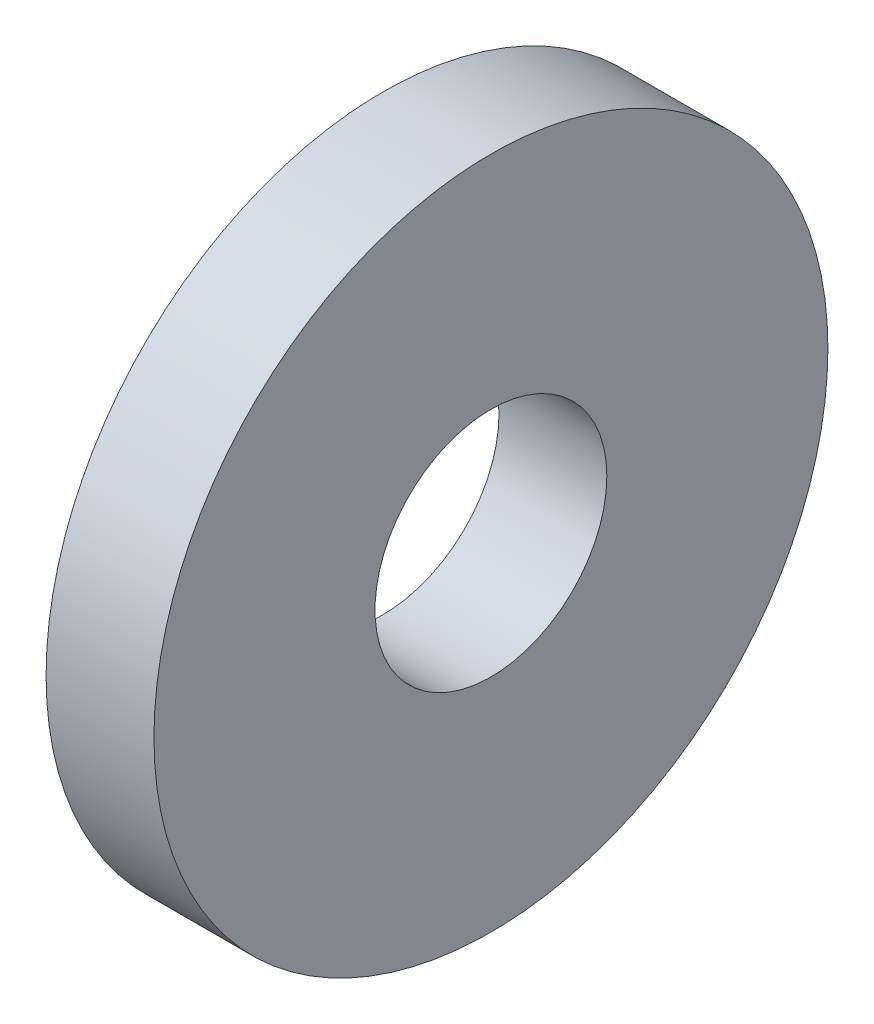
SolidWorks part; units mm, degrees
ref_plane "Front Plane" through (0, 0, 0) normal (0, 0, 1) x (1, 0, 0)
ref_plane "Top Plane" through (0, 0, 0) normal (0, 1, 0) x (1, 0, 0)
ref_plane "Right Plane" through (0, 0, 0) normal (1, 0, 0) x (0, 0, -1)
sketch "Sketch1" plane through (0, 0, 0) normal (1, 0, 0) x (0, 0, -1)
  circle A0 centre (0, 0) radius 6.35
  circle A1 centre (0, 0) radius 2.1844
  dimension "OD" = 12.7
  dimension "ID" = 4.3688
extrude "Boss-Extrude1" add sketch "Sketch1" along normal blind 2.032
